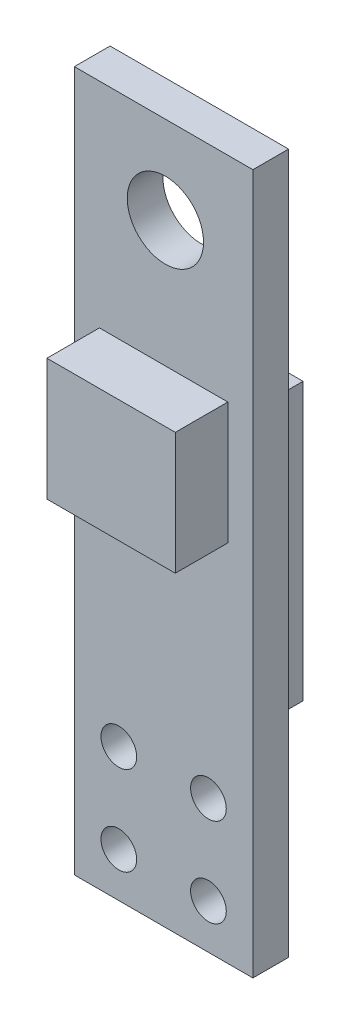
SolidWorks part; units mm, degrees
ref_plane "Front Plane" through (0, 0, 0) normal (0, 0, 1) x (1, 0, 0)
ref_plane "Top Plane" through (0, 0, 0) normal (0, 1, 0) x (1, 0, 0)
ref_plane "Right Plane" through (0, 0, 0) normal (1, 0, 0) x (0, 0, -1)
sketch "Sketch1" plane through (0, 0, 0) normal (0, 0, 1) x (1, 0, 0)
  line L0 (0, 10) -> (0, 50010) construction
  line L1 (-2.55, -10) -> (2.55, -10)
  line L2 (-2.55, -10) -> (-2.55, 10)
  line L3 (-2.55, 10) -> (2.55, 10)
  line L4 (2.55, -10) -> (2.55, 10)
  line L5 (-2.55, -10) -> (2.55, 10) construction
  line L6 (-2.55, 10) -> (2.55, -10) construction
  line L7 (-1.7, 3.8667) -> (1.7, 3.8667) construction
  line L8 (-1.7, 3.8667) -> (-1.7, 0.4333) construction
  line L9 (-1.7, 0.4333) -> (1.7, 0.4333) construction
  line L10 (1.7, 3.8667) -> (1.7, 0.4333) construction
  line L11 (-1.7, 3.8667) -> (1.7, 0.4333) construction
  line L12 (-1.7, 0.4333) -> (1.7, 3.8667) construction
  line L14 (-1.28, -8.73) -> (1.28, -8.73) construction
  line L15 (-1.28, -8.73) -> (-1.28, -6.19) construction
  line L16 (-1.28, -6.19) -> (1.28, -6.19) construction
  line L17 (1.28, -8.73) -> (1.28, -6.19) construction
  line L18 (-1.28, -8.73) -> (1.28, -6.19) construction
  line L19 (-1.28, -6.19) -> (1.28, -8.73) construction
  circle A0 centre (0.05, 7.5) radius 1.09
  circle A1 centre (-1.28, -6.19) radius 0.51
  circle A2 centre (1.28, -6.19) radius 0.51
  circle A3 centre (1.28, -8.73) radius 0.51
  circle A4 centre (-1.28, -8.73) radius 0.51
  point P0 (0, 0)
  point P9 (0, 2.15)
  point P16 (0, 10)
  point P17 (0, -7.46)
  dimension "D5" = 2.18
  dimension "D12" = 1.02
  dimension "D1" = 20
  dimension "D2" = 5.1
  dimension "D3" = 2.5
  dimension "D4" = 2.5
  dimension "D6" = 3.4
  dimension "D7" = 3.4333
  dimension "D8" = 12.15
  dimension "D9" = 1.27
  dimension "D10" = 1.27
  dimension "D11" = 2.54
extrude "Boss-Extrude1" add sketch "Sketch1" along normal blind 1.02
sketch "Sketch2" plane through (0, 0, 1.02) normal (0, 0, 1) x (1, 0, 0)
  line L0 (0, 10.3061) -> (0, 50010.3061) construction
  line L5 (-2.55, -10) -> (2.55, -10) construction
  line L7 (-1.8336, 3.8933) -> (1.8336, 3.8933)
  line L8 (-1.8336, 3.8933) -> (-1.8336, 0.4067)
  line L9 (-1.8336, 0.4067) -> (1.8336, 0.4067)
  line L10 (1.8336, 3.8933) -> (1.8336, 0.4067)
  line L11 (-1.8336, 3.8933) -> (1.8336, 0.4067) construction
  line L12 (-1.8336, 0.4067) -> (1.8336, 3.8933) construction
  point P8 (0, 2.15)
  dimension "D1" = 12.15
extrude "Boss-Extrude2" add sketch "Sketch2" along normal blind 1.5
sketch "Sketch3" plane through (0, 0, 0) normal (0, 0, -1) x (-1, 0, 0)
  line L0 (0, 0) -> (0, 50000) construction
  line L1 (-1.8635, 3.3607) -> (1.8635, 3.3607)
  line L2 (-1.8635, 3.3607) -> (-1.8635, -4.5458)
  line L3 (-1.8635, -4.5458) -> (1.8635, -4.5458)
  line L4 (1.8635, 3.3607) -> (1.8635, -4.5458)
  line L5 (-1.8635, 3.3607) -> (1.8635, -4.5458) construction
  line L6 (-1.8635, -4.5458) -> (1.8635, 3.3607) construction
  point P0 (0, -0.5926)
extrude "Boss-Extrude3" add sketch "Sketch3" along normal blind 1.1
